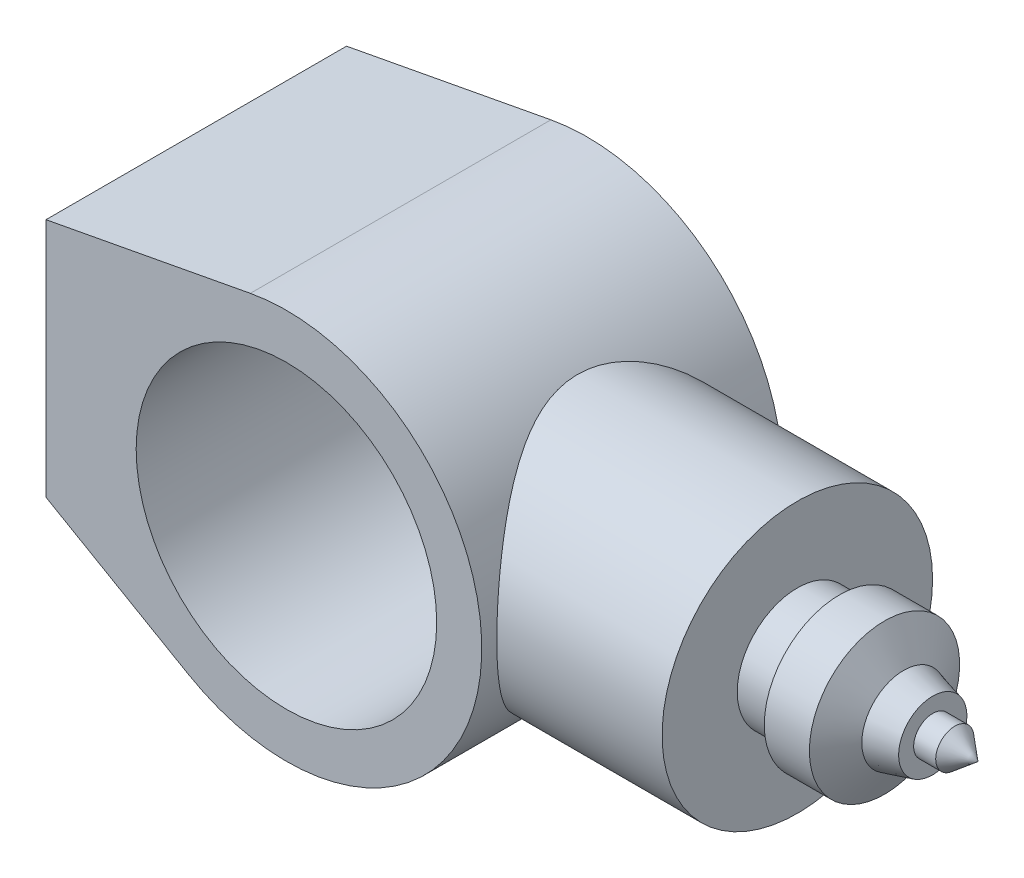
SolidWorks part; units mm, degrees
ref_plane "Ön Düzlem" through (0, 0, 0) normal (0, 0, 1) x (1, 0, 0)
ref_plane "Üst Düzlem" through (0, 0, 0) normal (0, 1, 0) x (1, 0, 0)
ref_plane "Sağ Düzlem" through (0, 0, 0) normal (1, 0, 0) x (0, 0, -1)
sketch "Çizim1" plane through (0, 0, 0) normal (0, 0, 1) x (1, 0, 0)
  line L0 (-80, -28.8907) -> (-80, 51.1093)
  line L1 (-80, -28.8907) -> (-32.4794, -56.3035)
  line L2 (-80, 51.1093) -> (-12, 63.8827)
  arc A0 (-32.4794, -56.3035) -> (-12, 63.8827) centre (0, 0) ccw
  circle A1 centre (0, 0) radius 50
  point P7 (-80, 11.1093)
  dimension "D1" = 130
  dimension "D2" = 100
  dimension "D3" = 80
  dimension "D4" = 80
  dimension "D5" = 68
extrude "Yükseklik-Ekstrüzyon1" add sketch "Çizim1" along normal mid plane 100
ref_plane "Düzlem1" through (120, 0, 0) normal (1, 0, 0) x (0, 0, -1)
sketch "Çizim2" plane through (120, 0, 0) normal (1, 0, 0) x (0, 0, -1)
  circle A0 centre (0, 0) radius 45
  dimension "D1" = 90
extrude "Yükseklik-Ekstrüzyon2" add sketch "Çizim2" against normal up to next
sketch "Çizim3" plane through (0, 0, 0) normal (0, 0, 1) x (1, 0, 0)
  line L0 (0, 0) -> (240, 0) construction
  line L1 (164.3853, -6.3512) -> (172.3853, -6.3512)
  line L2 (120, -45) -> (120, 45) construction
  line L3 (120, 0) -> (120, -20)
  line L4 (120, -20) -> (134, -20)
  line L5 (134, -20) -> (134, -25)
  line L6 (134, -25) -> (149, -25)
  line L7 (149, -25) -> (155.3859, -13.9393)
  line L8 (155.3859, -13.9393) -> (165.0451, -11.3512)
  line L9 (165.0451, -11.3512) -> (165.0451, -6.3512)
  line L10 (165.0451, -6.3512) -> (164.3853, -6.3512)
  line L13 (172.3853, -6.3512) -> (180.1095, 0)
  line L14 (180.1095, 0) -> (120, 0)
  point P3 (120, 0)
  dimension "D1" = 20
  dimension "D2" = 14
  dimension "D3" = 5
  dimension "D4" = 15
  dimension "D5" = 10
  dimension "D6" = 5
  dimension "D7" = 120
  dimension "D8" = 8
  dimension "D9" = 10
revolve "Döndür1" add sketch "Çizim3" angle 360 about L0
